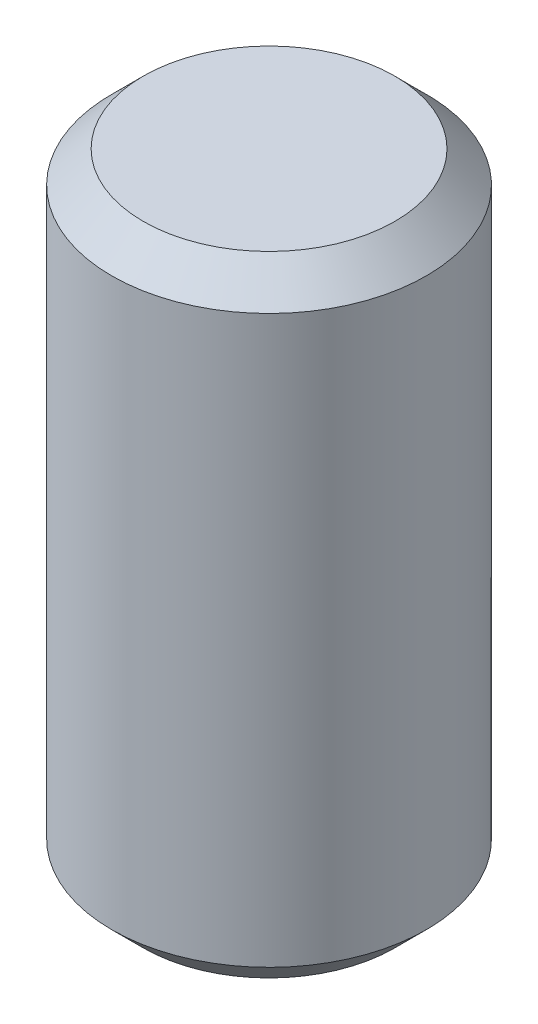
SolidWorks part; units mm, degrees
ref_plane "Front Plane" through (0, 0, 0) normal (0, 0, 1) x (1, 0, 0)
ref_plane "Top Plane" through (0, 0, 0) normal (0, 1, 0) x (1, 0, 0)
ref_plane "Right Plane" through (0, 0, 0) normal (1, 0, 0) x (0, 0, -1)
sketch "Sketch1" plane through (0, 0, 0) normal (0, 1, 0) x (1, 0, 0)
  circle A0 centre (-12.2505, 8.5444) radius 5
  dimension "D1" = 10
extrude "Boss-Extrude2" add sketch "Sketch1" along normal blind 20
chamfer "Chamfer1" distance 1 angle 45 2 edges at (-12.2505, 0, -3.5444) (-12.2505, 20, -3.5444)
